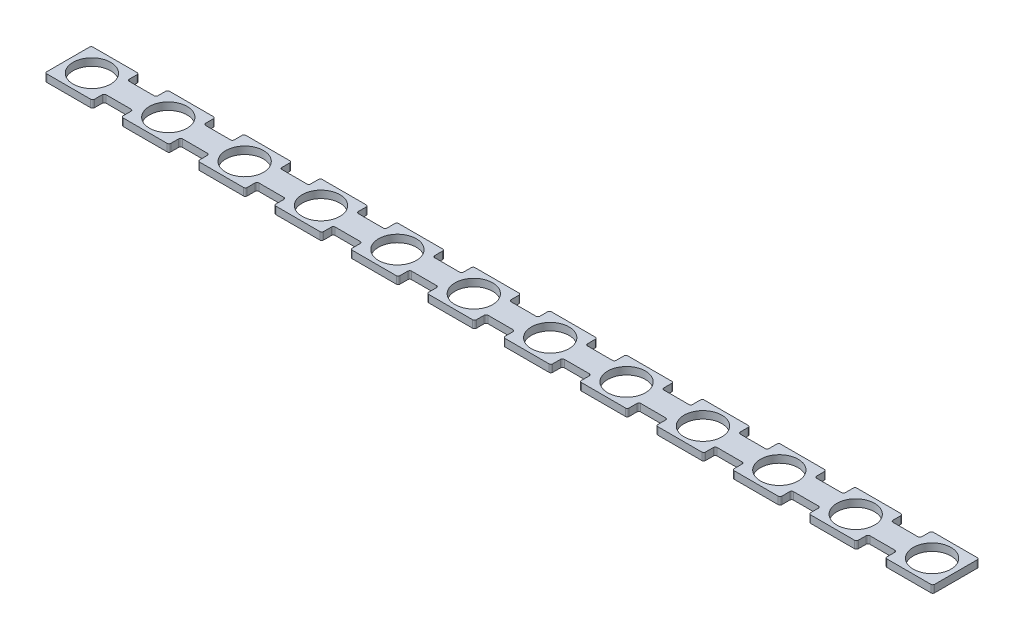
SolidWorks part; units mm, degrees
material "Chrome Stainless Steel"
ref_plane "Front Plane" through (0, 0, 0) normal (0, 0, 1) x (1, 0, 0)
ref_plane "Top Plane" through (0, 0, 0) normal (0, 1, 0) x (1, 0, 0)
ref_plane "Right Plane" through (0, 0, 0) normal (1, 0, 0) x (0, 0, -1)
sketch "BaseS" plane through (0, 0, 0) normal (0, 1, 0) x (1, 0, 0)
  line L1 (-47.75, 2.5) -> (47.75, 2.5)
  line L2 (-47.95, 2.3) -> (-47.95, -2.3)
  line L3 (-47.75, -2.5) -> (47.75, -2.5)
  line L4 (47.95, 2.3) -> (47.95, -2.3)
  line L5 (-47.95, 2.5) -> (47.95, -2.5) construction
  line L6 (-47.95, -2.5) -> (47.95, 2.5) construction
  arc A1 (-47.95, -2.3) -> (-47.75, -2.5) centre (-47.75, -2.3) ccw
  arc A2 (47.75, -2.5) -> (47.95, -2.3) centre (47.75, -2.3) ccw
  arc A3 (47.95, 2.3) -> (47.75, 2.5) centre (47.75, 2.3) ccw
  arc A4 (-47.75, 2.5) -> (-47.95, 2.3) centre (-47.75, 2.3) ccw
  point P0 (0, 0)
  dimension "Radius" = 0.2
  dimension "Width" = 5
  dimension "Length" = 95.9
extrude "Base" add sketch "BaseS" along normal mid plane 0.8
sketch "NotchS" plane through (0, 0.4, 0) normal (0, 1, 0) x (1, 0, 0)
  line L0 (-47.75, 2.5) -> (47.75, 2.5) construction
  line L1 (-42.6, 1.25) -> (-39.9, 1.25)
  line L2 (-42.8, 1.45) -> (-42.8, 2.2998)
  line L3 (-42.8, 2.5) -> (-39.7, 2.5)
  line L4 (-39.7, 1.45) -> (-39.7, 2.2998)
  line L5 (-42.8, 1.25) -> (-39.7, 2.5) construction
  line L6 (-42.8, 2.5) -> (-39.7, 1.25) construction
  line L7 (-47.95, 2.3) -> (-47.95, -2.3) construction
  line L8 (-42.8, 2.5) -> (-43.0002, 2.5)
  line L9 (47.75, 2.5) -> (-47.75, 2.5) construction
  line L10 (-39.7, 2.5) -> (-39.4998, 2.5)
  line L11 (-41.25, 1.875) -> (-41.25, 2.5) construction
  line L12 (-41.25, 1.25) -> (-41.25, 1.875) construction
  arc A0 (-39.7, 1.45) -> (-39.9, 1.25) centre (-39.9, 1.45) cw
  arc A1 (-42.8, 1.45) -> (-42.6, 1.25) centre (-42.6, 1.45) ccw
  arc A2 (-43.0002, 2.5) -> (-42.8, 2.2998) centre (-43.0002, 2.2998) cw
  arc A3 (-39.4998, 2.5) -> (-39.7, 2.2998) centre (-39.4998, 2.2998) ccw
  point P0 (-41.25, 1.875)
  dimension "D1" = 0.2
  dimension "D2" = 0.2002
  dimension "Length" = 3.1
  dimension "Width" = 1.25
  dimension "XDim" = 6.7
extrude "Notch" cut sketch "NotchS" against normal through all
mirror "NotchVM" about plane through (0, 0, 0) normal (0, 0, 1) of "Notch"
sketch "HoleS" plane through (0, 0.4, 0) normal (0, 1, 0) x (1, 0, 0)
  line L0 (-47.95, 0) -> (-45.375, 0) construction
  line L1 (-47.95, 2.3) -> (-47.95, -2.3) construction
  line L2 (-42.8, 1.45) -> (-47.95, 1.45) construction
  line L3 (-47.95, 2.3) -> (-47.95, -2.3) construction
  line L4 (-45.375, 0) -> (-45.375, 1.45) construction
  circle A0 centre (-45.375, 0) radius 2.0365
  dimension "D1" = 4.0731
  dimension "D2" = 2.575
extrude "Hole" cut sketch "HoleS" against normal through all
pattern_linear "HoleLP" count 12 spacing 8.25 along (1, 0, 0) of "Hole"
pattern_linear "NotchLP" count 11 spacing 8.25 along (1, 0, 0) of "Notch", "NotchVM"
equation "\"NumInstances@NotchLP\"=\"NumInstances@HoleLP\"-1"
